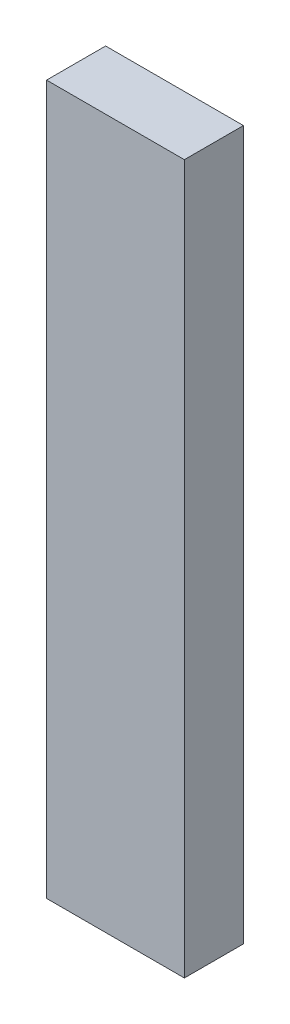
SolidWorks part; units mm, degrees
material "Pine"
ref_plane "Front Plane" through (0, 0, 0) normal (0, 0, 1) x (1, 0, 0)
ref_plane "Top Plane" through (0, 0, 0) normal (0, 1, 0) x (1, 0, 0)
ref_plane "Right Plane" through (0, 0, 0) normal (1, 0, 0) x (0, 0, -1)
sketch "Sketch1" plane through (0, 0, 0) normal (0, 1, 0) x (1, 0, 0)
  line L1 (0, 0) -> (88.9, 0)
  line L2 (0, 0) -> (0, 38.1)
  line L3 (0, 38.1) -> (88.9, 38.1)
  line L4 (88.9, 0) -> (88.9, 38.1)
  dimension "D1" = 88.9
  dimension "D2" = 38.1
extrude "Boss-Extrude1" add sketch "Sketch1" along normal blind 457.2
